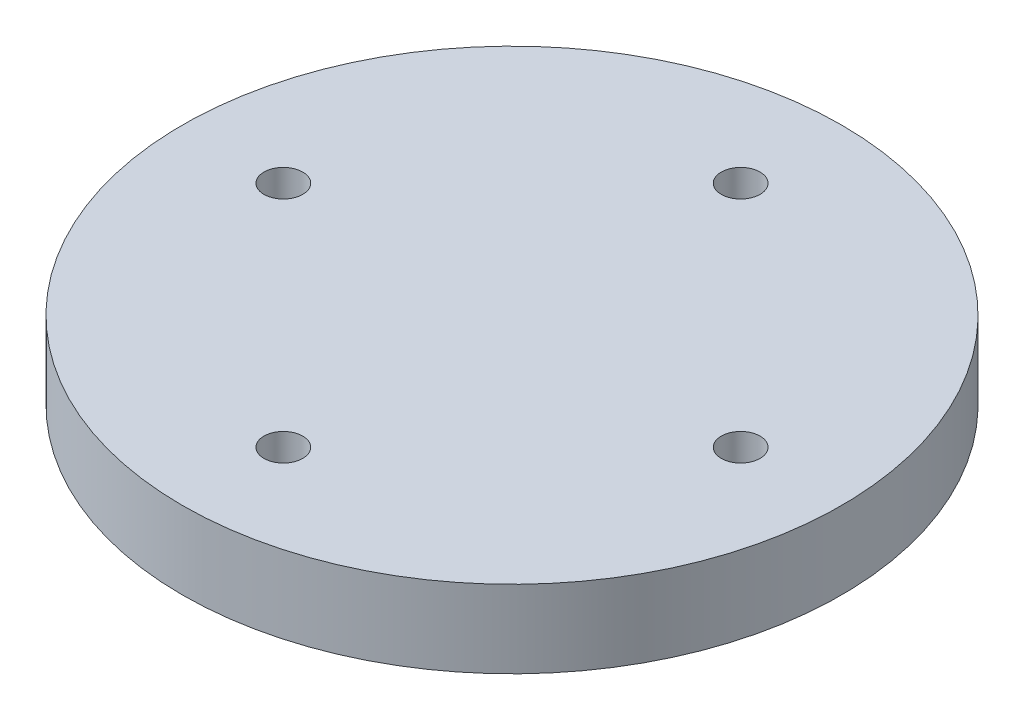
SolidWorks part; units mm, degrees
ref_plane "Спереди" through (0, 0, 0) normal (0, 0, 1) x (1, 0, 0)
ref_plane "Сверху" through (0, 0, 0) normal (0, 1, 0) x (1, 0, 0)
ref_plane "Справа" through (0, 0, 0) normal (1, 0, 0) x (0, 0, -1)
sketch "Эскиз1" plane through (0, 0, 0) normal (0, 1, 0) x (1, 0, 0)
  circle A0 centre (0, 0) radius 42.5
extrude "Вытянуть1" add sketch "Эскиз1" along normal blind 10
sketch "Эскиз2" plane through (0, 0, 0) normal (0, -1, 0) x (1, 0, 0)
  circle A0 centre (-29.4896, 0) radius 7
  circle A1 centre (0, 29.4896) radius 7
  circle A2 centre (29.4896, 0) radius 7
  circle A3 centre (0, -29.4896) radius 7
extrude "Вырез-Вытянуть1" cut sketch "Эскиз2" against normal blind 6
sketch "Эскиз3" plane through (0, 6, 0) normal (0, -1, 0) x (1, 0, 0)
  circle A0 centre (-29.4896, 0) radius 2.5
  circle A1 centre (0, 29.4896) radius 2.5
  circle A2 centre (29.4896, 0) radius 2.5
  circle A3 centre (0, -29.4896) radius 2.5
extrude "Вырез-Вытянуть2" cut sketch "Эскиз3" against normal blind 6
